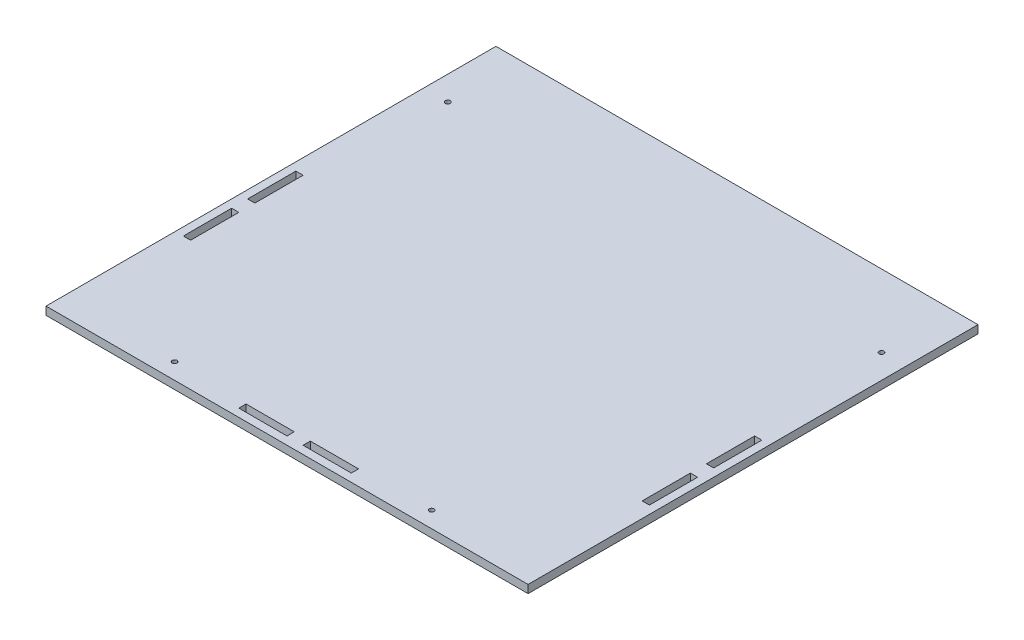
SolidWorks part; units mm, degrees
ref_plane "Front Plane" through (0, 0, 0) normal (0, 0, 1) x (1, 0, 0)
ref_plane "Top Plane" through (0, 0, 0) normal (0, 1, 0) x (1, 0, 0)
ref_plane "Right Plane" through (0, 0, 0) normal (1, 0, 0) x (0, 0, -1)
sketch "Sketch1" plane through (0, 0, 0) normal (0, 1, 0) x (1, 0, 0)
  line L0 (0, 0) -> (0, 50000) construction
  line L1 (-150, -140) -> (150, -140)
  line L2 (-150, -140) -> (-150, 140)
  line L3 (-150, 140) -> (150, 140)
  line L4 (150, -140) -> (150, 140)
  line L5 (-150, -140) -> (150, 140) construction
  line L6 (-150, 140) -> (150, -140) construction
  line L7 (0, 0) -> (50000, 0) construction
  line L8 (-5, -135) -> (-35, -135)
  line L9 (5, -130.5) -> (35, -130.5)
  line L10 (5, -130.5) -> (5, -135)
  line L11 (5, -135) -> (35, -135)
  line L12 (35, -130.5) -> (35, -135)
  line L13 (-35, -130.5) -> (-35, -135)
  line L14 (-5, -130.5) -> (-35, -130.5)
  line L15 (-5, -130.5) -> (-5, -135)
  line L16 (150, -24.5) -> (-49850, -24.5) construction
  line L17 (140.5, -29.5) -> (145, -29.5)
  line L18 (140.5, -29.5) -> (140.5, -59.5)
  line L19 (140.5, -59.5) -> (145, -59.5)
  line L20 (145, -29.5) -> (145, -59.5)
  line L21 (140.5, 10.5) -> (145, 10.5)
  line L22 (145, -19.5) -> (145, 10.5)
  line L23 (140.5, -19.5) -> (145, -19.5)
  line L24 (140.5, -19.5) -> (140.5, 10.5)
  line L25 (-140.5, -59.5) -> (-145, -59.5)
  line L26 (-145, -29.5) -> (-145, -59.5)
  line L27 (-140.5, -29.5) -> (-145, -29.5)
  line L28 (-140.5, -29.5) -> (-140.5, -59.5)
  line L29 (-140.5, -19.5) -> (-140.5, 10.5)
  line L30 (-140.5, -19.5) -> (-145, -19.5)
  line L31 (-145, -19.5) -> (-145, 10.5)
  line L32 (-140.5, 10.5) -> (-145, 10.5)
  circle A0 centre (-134.97, 95) radius 1.5
  circle A1 centre (134.97, 95) radius 1.5
  circle A2 centre (80, -130) radius 1.5
  circle A3 centre (-80, -130) radius 1.5
  point P0 (0, 0)
  point P6 (-134.97, 95)
  point P15 (80, -130)
  dimension "D5" = 3
  dimension "D8" = 3
  dimension "D1" = 300
  dimension "D2" = 280
  dimension "D3" = 45
  dimension "D4" = 15.03
  dimension "D6" = 10
  dimension "D7" = 70
  dimension "D9" = 4.5
  dimension "D10" = 30
  dimension "D11" = 5
  dimension "D12" = 5
  dimension "D13" = 30
  dimension "D14" = 4.5
  dimension "D15" = 5
  dimension "D16" = 80.5
  dimension "D17" = 5
extrude "Boss-Extrude1" add sketch "Sketch1" along normal blind 5
